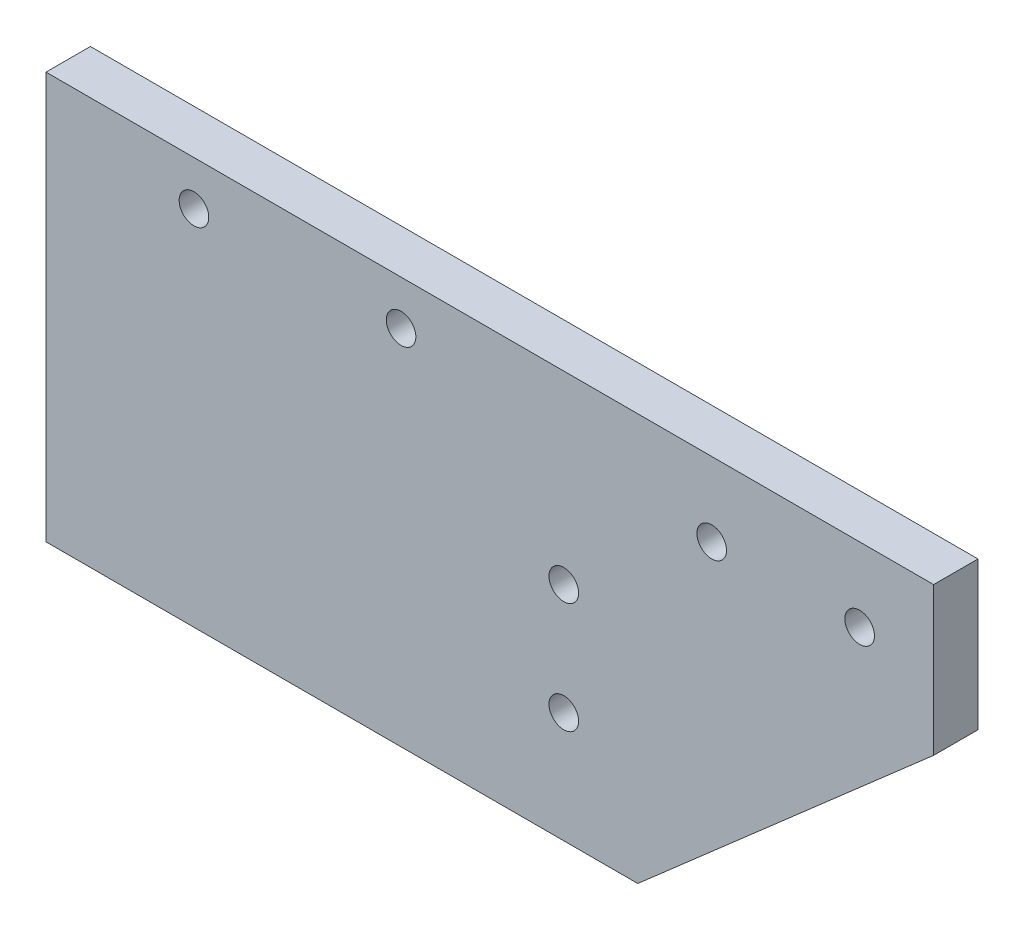
SolidWorks part; units mm, degrees
ref_plane "Front Plane" through (0, 0, 0) normal (0, 0, 1) x (1, 0, 0)
ref_plane "Top Plane" through (0, 0, 0) normal (0, 1, 0) x (1, 0, 0)
ref_plane "Right Plane" through (0, 0, 0) normal (1, 0, 0) x (0, 0, -1)
sketch "Sketch1" plane through (0, 0, 0) normal (0, 0, 1) x (1, 0, 0)
  line L0 (20, -55) -> (60, -20)
  line L1 (0, 0) -> (60, 0)
  line L2 (0, 0) -> (0, -55) construction
  line L3 (0, -55) -> (20, -55)
  line L4 (60, 0) -> (60, -20)
  line L5 (10, -55) -> (10, -40) construction
  line L6 (10, -40) -> (10, -25) construction
  line L7 (10, -25) -> (10, -10) construction
  line L8 (10, -10) -> (30, -10) construction
  line L9 (30, -10) -> (50, -10) construction
  line L10 (50, -10) -> (60, -10) construction
  line L11 (-60, 0) -> (-6, 0) construction
  line L12 (-60, -55) -> (0, -55)
  line L13 (-60, -55) -> (-60, 0)
  line L14 (-60, 0) -> (0, 0)
  line L15 (0, -55) -> (0, 0) construction
  line L16 (-60, 0) -> (-60, -6) construction
  line L17 (-60, -6) -> (-40, -6) construction
  line L18 (-6, 0) -> (-6, -6) construction
  line L19 (-6, 0) -> (-6, -12) construction
  line L20 (-6, -6) -> (-12, -6) construction
  circle A0 centre (50, -10) radius 2
  circle A1 centre (30, -10) radius 2
  circle A2 centre (10, -40) radius 2
  circle A3 centre (10, -25) radius 2
  circle A4 centre (-40, -6) radius 2
  circle A5 centre (-12, -6) radius 2
  dimension "D3" = 4
  dimension "D12" = 4
  dimension "D13" = 4
  dimension "D1" = 60
  dimension "D2" = 20
  dimension "D4" = 10
  dimension "D5" = 30
  dimension "D6" = 25
  dimension "D7" = 15
  dimension "D8" = 60
  dimension "D9" = 55
  dimension "D10" = 6
  dimension "D11" = 20
extrude "Boss-Extrude1" add sketch "Sketch1" along normal blind 6
